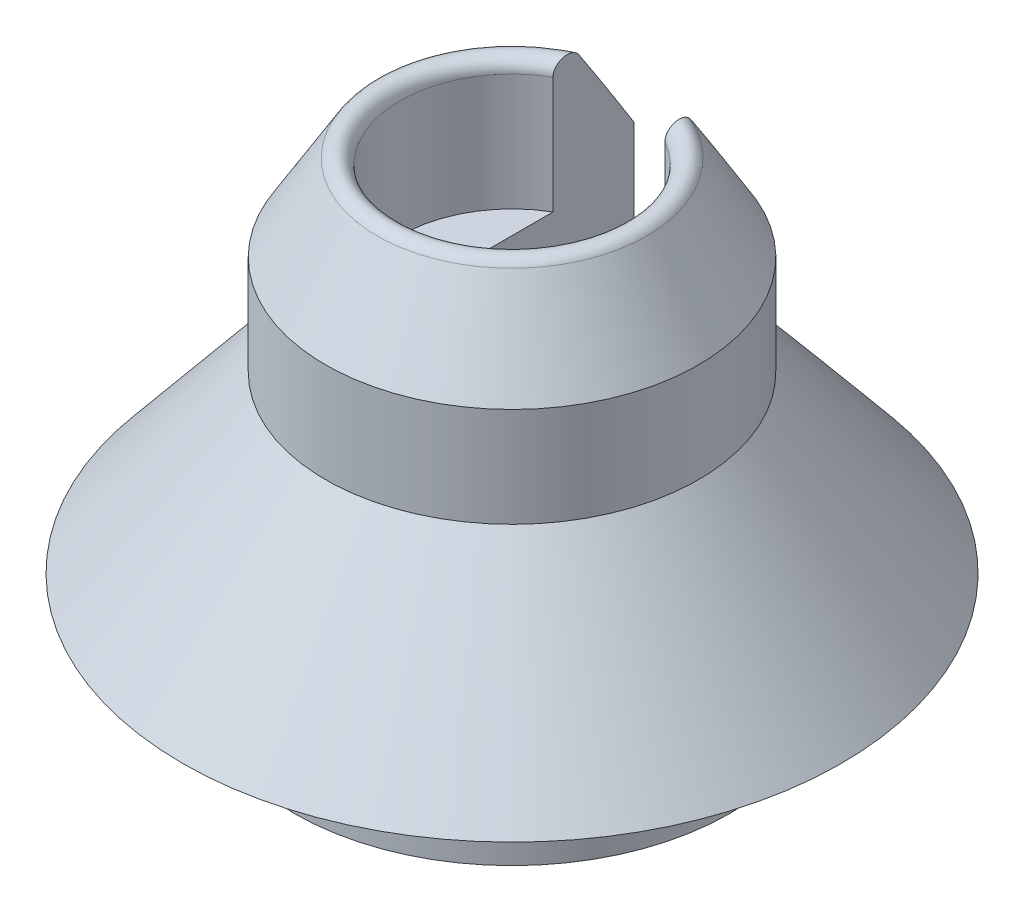
SolidWorks part; units mm, degrees
ref_plane "Front Plane" through (0, 0, 0) normal (0, 0, 1) x (1, 0, 0)
ref_plane "Top Plane" through (0, 0, 0) normal (0, 1, 0) x (1, 0, 0)
ref_plane "Right Plane" through (0, 0, 0) normal (1, 0, 0) x (0, 0, -1)
sketch "Sketch2" plane through (0, 0, 0) normal (0, 0, 1) x (1, 0, 0)
  line L0 (0, 0) -> (0, 29.0633) construction
  line L1 (-2.25, 13.5) -> (-2.25, 0)
  line L2 (-2.25, 0) -> (-8.75, 0)
  line L3 (-8.75, 0) -> (-8.75, 4)
  line L4 (-8.75, 4) -> (-13.25, 4)
  line L5 (-2.25, 13.5) -> (-4.5, 13.5)
  line L6 (-4.5, 13.5) -> (-4.5, 20)
  line L7 (-4.5, 20) -> (-7.5, 15)
  line L8 (-7.5, 15) -> (-7.5, 11)
  line L9 (-7.5, 11) -> (-13.25, 4)
  dimension "D1" = 11
  dimension "D2" = 13.5
  dimension "D3" = 4.5
  dimension "D4" = 4.5
  dimension "D5" = 6.5
  dimension "D6" = 4
  dimension "D7" = 8.75
  dimension "D8" = 3
  dimension "D9" = 7
  dimension "D10" = 5
revolve "Revolve1" add sketch "Sketch2" angle 360 about L0
fillet "Fillet1" radius 0.5 1 edges at (0, 20, -4.5)
sketch "Sketch3" plane through (0, 0, 0) normal (0, -1, 0) x (1, 0, 0)
  line L1 (-2.25, 0) -> (2.25, 0)
  line L2 (-2.25, 0) -> (-2.25, -28.7362)
  line L3 (-2.25, -28.7362) -> (2.25, -28.7362)
  line L4 (2.25, 0) -> (2.25, -28.7362)
  point P4 (0, 0)
  dimension "D1" = 4.5
extrude "Cut-Extrude1" cut sketch "Sketch3" against normal blind 28
